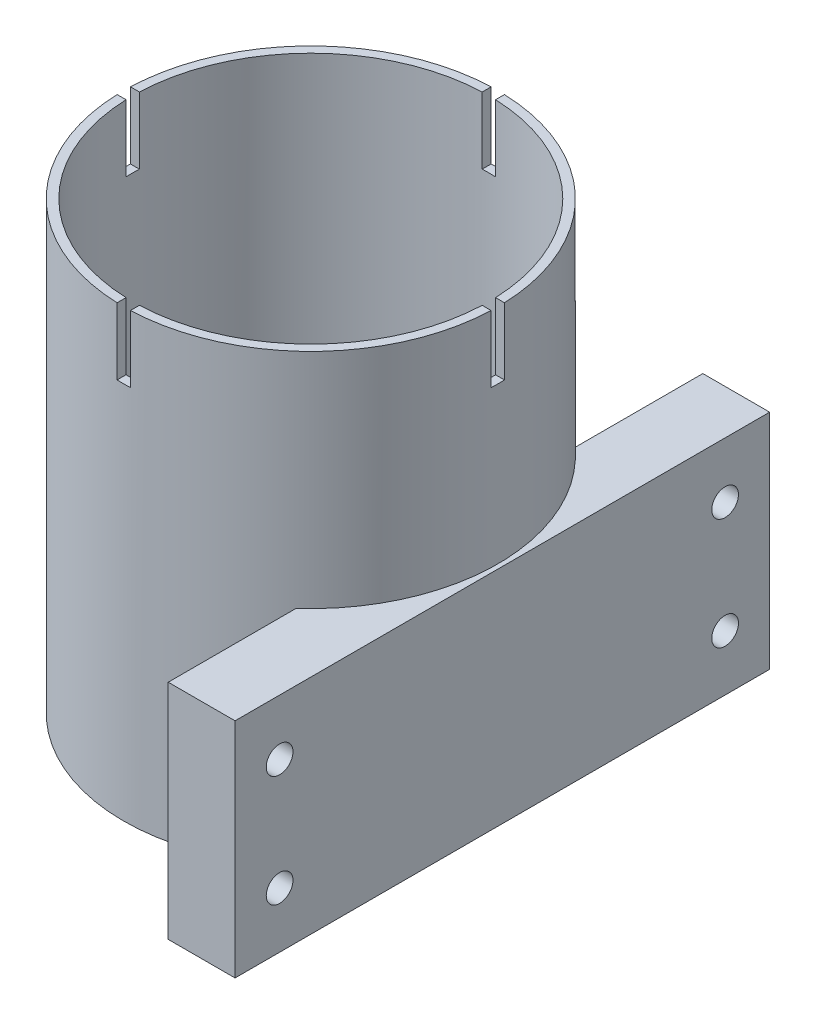
SolidWorks part; units mm, degrees
ref_plane "Plano frontal" through (0, 0, 0) normal (0, 0, 1) x (1, 0, 0)
ref_plane "Plano superior" through (0, 0, 0) normal (0, 1, 0) x (1, 0, 0)
ref_plane "Plano direito" through (0, 0, 0) normal (1, 0, 0) x (0, 0, -1)
sketch "Esboço1" plane through (0, 0, 0) normal (0, 1, 0) x (1, 0, 0)
  circle A0 centre (0, 0) radius 42
  dimension "D1" = 84
extrude "Ressalto-extrusão1" add sketch "Esboço1" along normal blind 100
sketch "Esboço2" plane through (0, 100, 0) normal (0, 1, 0) x (1, 0, 0)
  circle A0 centre (0, 0) radius 40
  dimension "D1" = 80
extrude "Corte-extrusão1" cut sketch "Esboço2" against normal blind 98
sketch "Esboço3" plane through (0, 0, 0) normal (0, -1, 0) x (1, 0, 0)
  circle A0 centre (0, 30) radius 5.5
  dimension "D1" = 11
  dimension "D2" = 30
extrude "Corte-extrusão2" cut sketch "Esboço3" against normal through all
sketch "Esboço4" plane through (0, 0, 0) normal (0, -1, 0) x (1, 0, 0)
  circle A0 centre (0, 0) radius 10
  dimension "D1" = 20
extrude "Corte-extrusão3" cut sketch "Esboço4" against normal through all
sketch "Esboço5" plane through (0, 100, 0) normal (0, 1, 0) x (1, 0, 0)
  line L0 (1.5, 1.5) -> (52.9403, 1.5)
  line L1 (-52.9403, -1.5) -> (-1.5, -1.5)
  line L2 (-52.9403, -1.5) -> (-52.9403, 1.5)
  line L3 (-52.9403, 1.5) -> (-1.5, 1.5)
  line L4 (52.9403, -1.5) -> (52.9403, 1.5)
  line L5 (1.5, -1.5) -> (52.9403, -1.5)
  line L7 (1.5, 46.2989) -> (-1.5, 46.2989)
  line L8 (1.5, 46.2989) -> (1.5, 1.5)
  line L9 (1.5, -46.2989) -> (-1.5, -46.2989)
  line L10 (-1.5, 46.2989) -> (-1.5, 1.5)
  line L15 (1.5, -1.5) -> (1.5, -46.2989)
  line L16 (-1.5, -1.5) -> (-1.5, -46.2989)
  circle A0 centre (0, 0) radius 40 construction
  point P0 (0, 0)
  point P6 (0, 0)
  dimension "D1" = 3
  dimension "D2" = 3
  dimension "D3" = 1.5
  dimension "D4" = 1.5
extrude "Corte-extrusão4" cut sketch "Esboço5" against normal blind 15
sketch "Esboço8" plane through (0, 0, 0) normal (0, -1, 0) x (1, 0, 0)
  line L0 (28, 31.305) -> (28, 60)
  line L1 (28, -60) -> (43, -60)
  line L2 (28, -60) -> (28, -31.305)
  line L3 (28, 60) -> (43, 60)
  line L4 (43, -60) -> (43, 60)
  circle A0 centre (0, 0) radius 42 construction
  arc A1 (28, -31.305) -> (28, 31.305) centre (0, 0) ccw
  point P0 (43, 0)
  dimension "D1" = 15
  dimension "D2" = 120
  dimension "D3" = 43
extrude "Ressalto-extrusão3" add sketch "Esboço8" against normal blind 50 contours L4 L3 L0 A1 L2 L1
sketch "Esboço9" plane through (28, 0, 0) normal (-1, 0, 0) x (0, 0, 1)
  line L1 (31.305, 50) -> (60, 50) construction
  line L2 (60, 50) -> (60, 0) construction
  line L3 (0, -6.655) -> (0, 65.8917) construction
  circle A0 centre (50, 37.5) radius 3
  circle A1 centre (50, 12.5) radius 3
  circle A2 centre (-50, 12.5) radius 3
  circle A3 centre (-50, 37.5) radius 3
  dimension "D1" = 6
  dimension "D2" = 25
  dimension "D3" = 12.5
  dimension "D4" = 10
extrude "Corte-extrusão5" cut sketch "Esboço9" against normal through all
